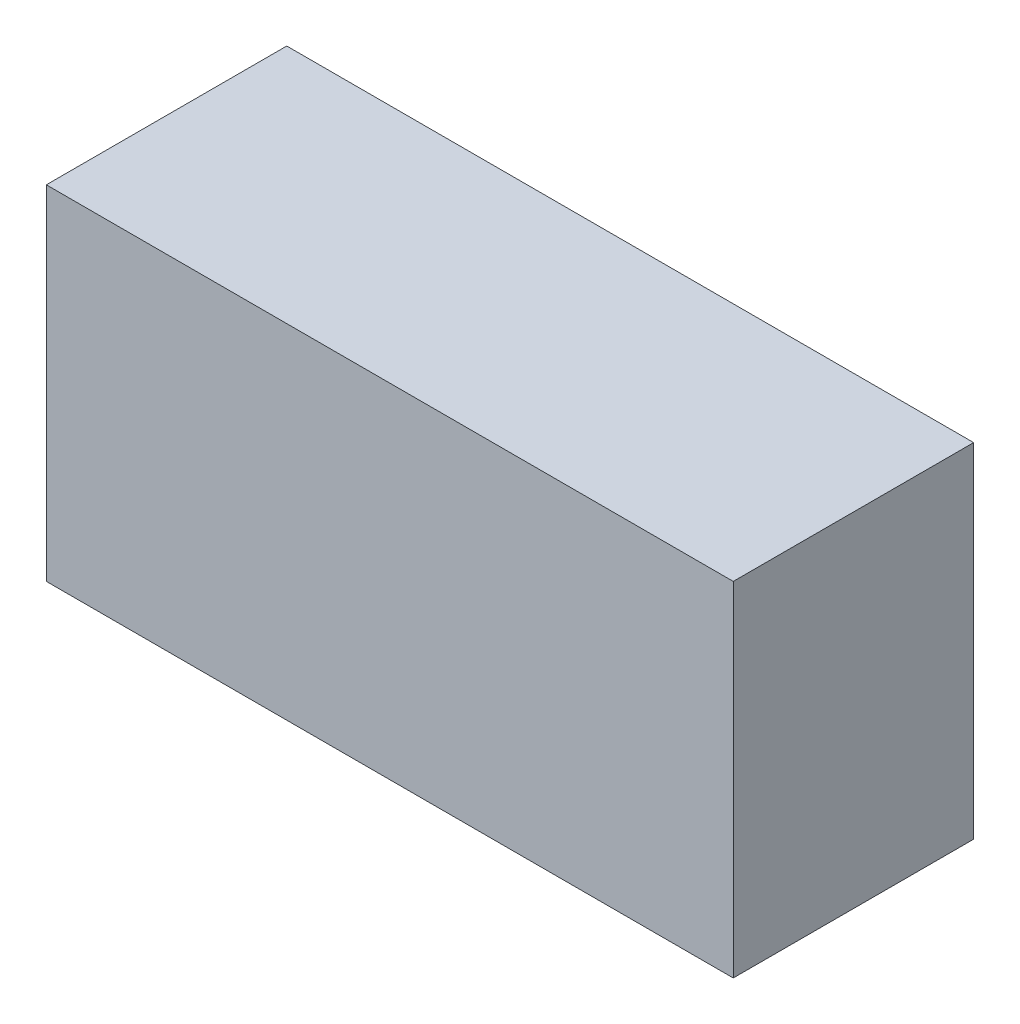
SolidWorks part; units mm, degrees
ref_plane "Front Plane" through (0, 0, 0) normal (0, 0, 1) x (1, 0, 0)
ref_plane "Top Plane" through (0, 0, 0) normal (0, 1, 0) x (1, 0, 0)
ref_plane "Right Plane" through (0, 0, 0) normal (1, 0, 0) x (0, 0, -1)
sketch "Sketch3" plane through (0, 0, 0) normal (0, 0, 1) x (1, 0, 0)
  line L5 (-30, -15) -> (30, -15)
  line L6 (-30, -15) -> (-30, 15)
  line L7 (-30, 15) -> (30, 15)
  line L8 (30, -15) -> (30, 15)
  line L9 (-30, -15) -> (30, 15) construction
  line L10 (-30, 15) -> (30, -15) construction
  point P0 (0, 0)
  dimension "D1" = 30
  dimension "D2" = 60
extrude "Boss-Extrude1" add sketch "Sketch3" along normal blind 21
